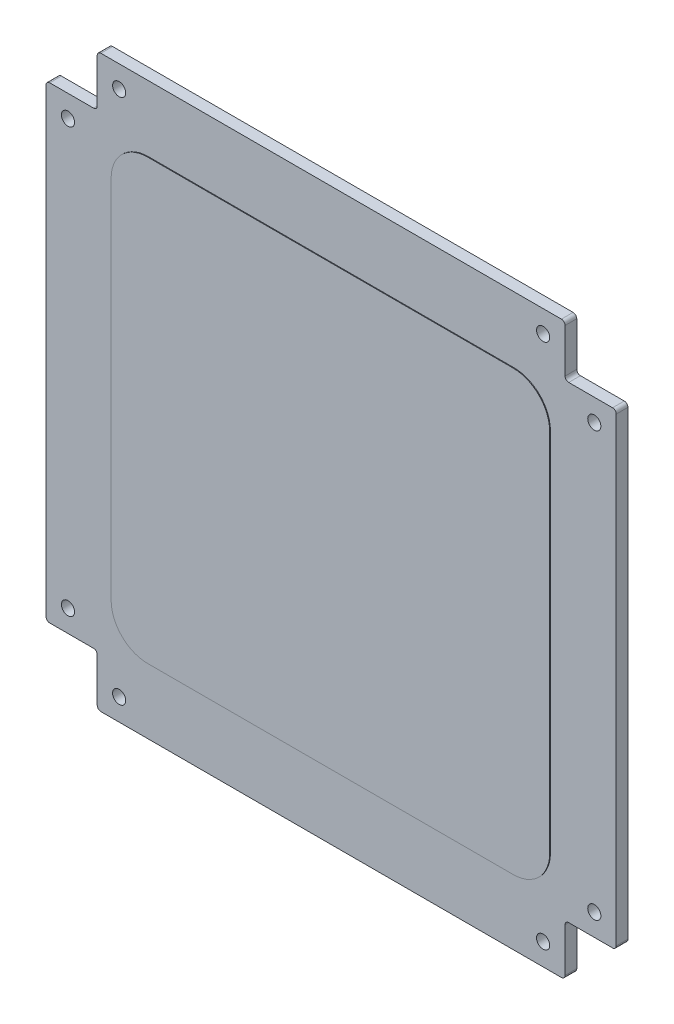
SolidWorks part; units mm, degrees
material "PET"
ref_plane "Front Plane" through (0, 0, 0) normal (0, 0, 1) x (1, 0, 0)
ref_plane "Top Plane" through (0, 0, 0) normal (0, 1, 0) x (1, 0, 0)
ref_plane "Right Plane" through (0, 0, 0) normal (1, 0, 0) x (0, 0, -1)
sketch "Sketch1" plane through (0, 0, 0) normal (0, 0, 1) x (1, 0, 0)
  line L0 (-32, 38.5) -> (-32, 32.5)
  line L1 (-31.5, -39) -> (31.5, -39)
  line L2 (-39, 31.5) -> (-39, -31.5)
  line L3 (-31.5, 39) -> (31.5, 39)
  line L4 (39, -31.5) -> (39, 31.5)
  line L5 (32, -38.5) -> (32, -32.5)
  line L6 (32.5, -32) -> (38.5, -32)
  line L7 (-32.5, 32) -> (-38.5, 32)
  line L8 (32, 38.5) -> (32, 32.5)
  line L9 (32.5, 32) -> (38.5, 32)
  line L10 (-38.5, -32) -> (-32.5, -32)
  line L11 (-32, -32.5) -> (-32, -38.5)
  line L12 (-32.5, -32.5) -> (32.5, 32.5) construction
  line L13 (32.5, -32.5) -> (-32.5, 32.5) construction
  arc A0 (-31.5, 39) -> (-32, 38.5) centre (-31.5, 38.5) ccw
  arc A1 (31.5, 39) -> (32, 38.5) centre (31.5, 38.5) cw
  arc A2 (32, 32.5) -> (32.5, 32) centre (32.5, 32.5) ccw
  arc A3 (38.5, 32) -> (39, 31.5) centre (38.5, 31.5) cw
  arc A4 (31.5, -39) -> (32, -38.5) centre (31.5, -38.5) ccw
  arc A5 (32.5, -32) -> (32, -32.5) centre (32.5, -32.5) ccw
  arc A6 (38.5, -32) -> (39, -31.5) centre (38.5, -31.5) ccw
  arc A7 (-32, -38.5) -> (-31.5, -39) centre (-31.5, -38.5) ccw
  arc A8 (-32, -32.5) -> (-32.5, -32) centre (-32.5, -32.5) ccw
  arc A9 (-39, -31.5) -> (-38.5, -32) centre (-38.5, -31.5) ccw
  arc A10 (-38.5, 32) -> (-39, 31.5) centre (-38.5, 31.5) ccw
  arc A11 (-32.5, 32) -> (-32, 32.5) centre (-32.5, 32.5) ccw
  point P0 (0, 0)
  dimension "D4" = 0.5
  dimension "D1" = 7
  dimension "D2" = 7
  dimension "D3" = 7
  dimension "D5" = 7
  dimension "D6" = 7
  dimension "D7" = 7
  dimension "D8" = 7
  dimension "D9" = 7
  dimension "D10" = 78
  dimension "D11" = 78
extrude "Boss-Extrude1" add sketch "Sketch1" along normal blind 1.6
sketch "Esboço1" plane through (0, 0, 1.6) normal (0, 0, 1) x (1, 0, 0)
  line L1 (-25, -30) -> (25, -30)
  line L2 (-30, -25) -> (-30, 25)
  line L3 (-25, 30) -> (25, 30)
  line L4 (30, -25) -> (30, 25)
  line L5 (-25, -25) -> (25, 25) construction
  line L6 (-25, 25) -> (25, -25) construction
  arc A0 (-30, 25) -> (-25, 30) centre (-25, 25) cw
  arc A1 (25, 30) -> (30, 25) centre (25, 25) cw
  arc A2 (30, -25) -> (25, -30) centre (25, -25) cw
  arc A3 (-25, -30) -> (-30, -25) centre (-25, -25) cw
  point P0 (0, 0)
  dimension "D1" = 5
  dimension "D2" = 60
  dimension "D3" = 60
extrude "Boss-Extrude2" add sketch "Esboço1" along normal blind 0.1
hole_wizard "M1.6 Hole1-FixingStructure" positions "Sketch3" profile "Sketch2" hole size "M1.6" standard "DIN"
sketch "Sketch3" plane through (0, 0, 0) normal (0, 0, -1) x (-1, 0, 0)
  line L0 (-31.5, 39) -> (31.5, 39) construction
  line L1 (31.5, -39) -> (-31.5, -39) construction
  line L2 (-39, -31.5) -> (-39, 31.5) construction
  line L3 (39, 31.5) -> (39, -31.5) construction
  line L4 (-31.5, 39) -> (31.5, 39) construction
  line L5 (31.5, -39) -> (-31.5, -39) construction
  line L6 (39, 31.5) -> (39, -31.5) construction
  line L7 (-39, -31.5) -> (-39, 31.5) construction
  point P0 (-29, 36)
  point P2 (29, 36)
  point P4 (-29, -36)
  point P6 (29, -36)
  point P20 (36, 29)
  point P22 (36, -29)
  point P24 (-36, -29)
  point P26 (-36, 29)
  dimension "D1" = 3
  dimension "D2" = 3
  dimension "D3" = 10
  dimension "D4" = 10
  dimension "D5" = 10
  dimension "D6" = 10
  dimension "D7" = 3
  dimension "D8" = 3
sketch "Sketch2" plane through (29, 36, 0) normal (1, 0, 0) x (0, 1, 0)
  line L0 (0, 0) -> (0, 200.5408)
  line L1 (0, 200.5408) -> (0.9, 200)
  line L2 (0.9, 200) -> (0.9, 0)
  line L5 (0.9, 0) -> (0, 0)
  line L10 (0, 200.5408) -> (-0.9, 200) construction
  line L11 (0, -6.35) -> (0, 107.95) construction
  dimension "Hole Dia." = 1.8
  dimension "Hole Depth" = 200
  dimension "Drill Angle" = 118
